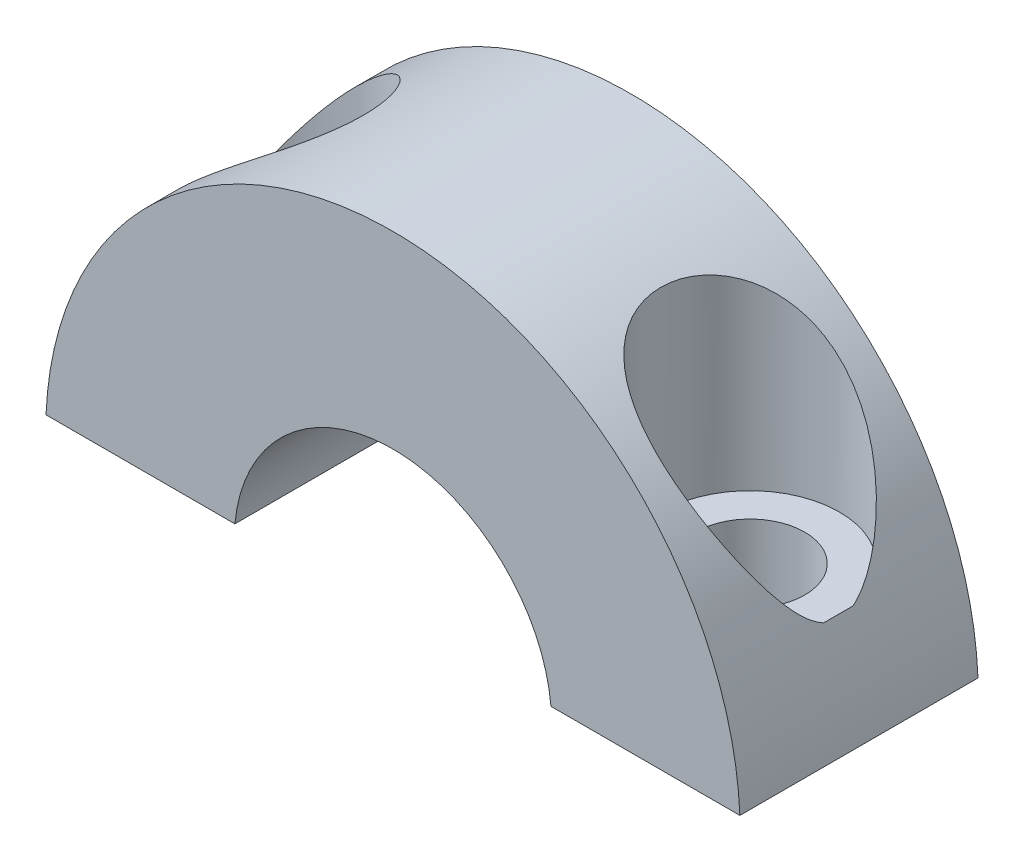
SolidWorks part; units mm, degrees
ref_plane "前视基准面" through (0, 0, 0) normal (0, 0, 1) x (1, 0, 0)
ref_plane "上视基准面" through (0, 0, 0) normal (0, 1, 0) x (1, 0, 0)
ref_plane "右视基准面" through (0, 0, 0) normal (1, 0, 0) x (0, 0, -1)
other "Configuration Table"
sketch "草图1" plane through (0, 0, 0) normal (0, 0, 1) x (1, 0, 0)
  line L2 (-17.4839, 0.75) -> (-7.9648, 0.75)
  line L3 (7.9648, 0.75) -> (17.4839, 0.75)
  arc A0 (17.4839, 0.75) -> (-17.4839, 0.75) centre (0, 0) ccw
  arc A1 (7.9648, 0.75) -> (-7.9648, 0.75) centre (0, 0) ccw
  dimension "D1" = 35
  dimension "D2" = 16
  dimension "D3" = 0.75
extrude "凸台-拉伸1" add sketch "草图1" along normal mid plane 12
sketch "草图2" plane through (0, 0.75, 0) normal (0, -1, 0) x (1, 0, 0)
  circle A0 centre (-12, 0) radius 2.75
  dimension "D1" = 5.5
  dimension "D2" = 12
extrude "切除-拉伸1" cut sketch "草图2" against normal through all
sketch "草图3" plane through (0, 0, 0) normal (0, 1, 0) x (1, 0, 0)
  circle A0 centre (-12, 0) radius 4.5
  dimension "D1" = 9
extrude "切除-拉伸2" cut sketch "草图3" along normal through all from offset 6
mirror "镜向1" about plane through (0, 0, 0) normal (1, 0, 0) of "切除-拉伸2", "切除-拉伸1"
